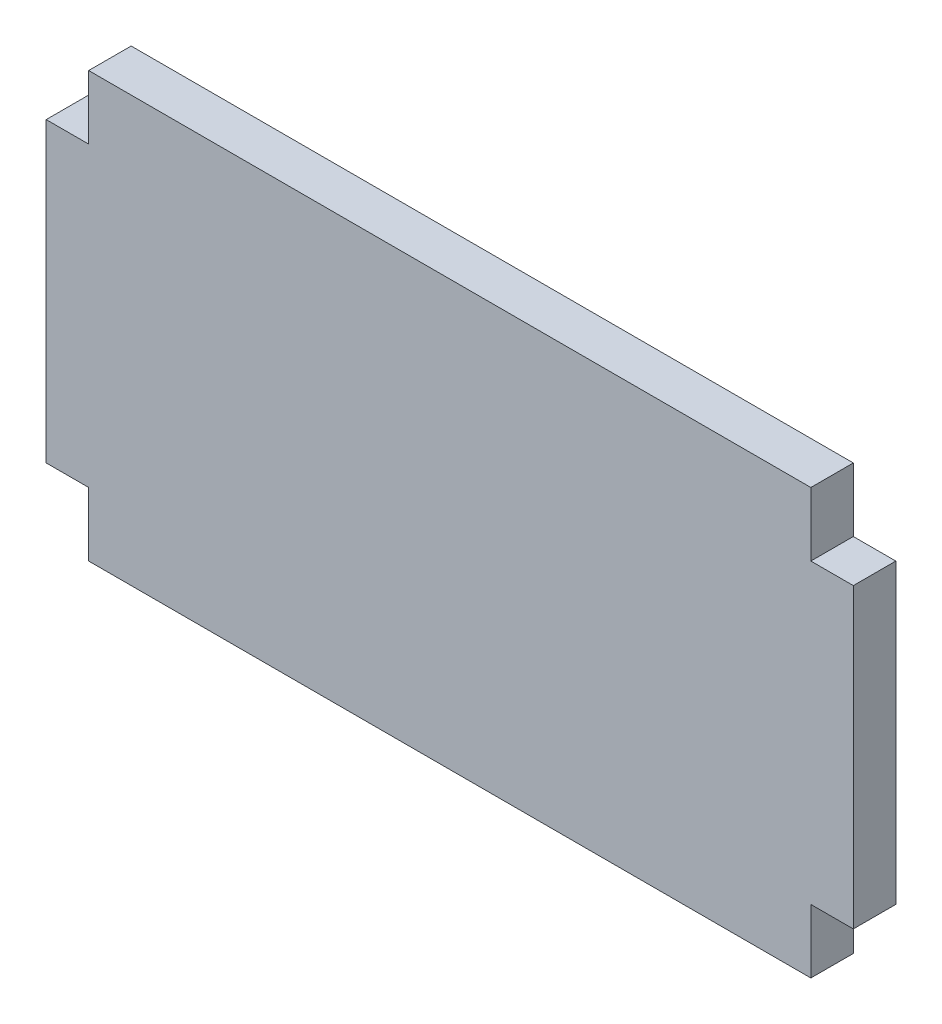
SolidWorks part; units mm, degrees
ref_plane "Alzado" through (0, 0, 0) normal (0, 0, 1) x (1, 0, 0)
ref_plane "Planta" through (0, 0, 0) normal (0, 1, 0) x (1, 0, 0)
ref_plane "Vista lateral" through (0, 0, 0) normal (1, 0, 0) x (0, 0, -1)
sketch "Croquis1" plane through (0, 0, 0) normal (0, 0, 1) x (1, 0, 0)
  line L0 (-47.5, 0) -> (47.5, 0) construction
  line L1 (-42.5, -25) -> (42.5, -25)
  line L2 (-42.5, -25) -> (-42.5, -17.5)
  line L3 (-42.5, 25) -> (42.5, 25)
  line L4 (42.5, -25) -> (42.5, -17.5)
  line L5 (-42.5, -25) -> (42.5, 25) construction
  line L6 (-42.5, 25) -> (42.5, -25) construction
  line L7 (-42.5, 17.5) -> (-42.5, 25)
  line L8 (-47.5, -17.5) -> (-42.5, -17.5)
  line L9 (-47.5, -17.5) -> (-47.5, 17.5)
  line L10 (-47.5, 17.5) -> (-42.5, 17.5)
  line L11 (42.5, 17.5) -> (42.5, 25)
  line L14 (42.5, -17.5) -> (47.5, -17.5)
  line L16 (42.5, 17.5) -> (47.5, 17.5)
  line L17 (47.5, -17.5) -> (47.5, 17.5)
  point P0 (0, 0)
  point P7 (-94.6371, 12.7325)
  dimension "D1" = 85
  dimension "D2" = 50
  dimension "D3" = 35
  dimension "D4" = 5
  dimension "D5" = 7.5
  dimension "D6" = 5
extrude "Saliente-Extruir1" add sketch "Croquis1" along normal blind 5
